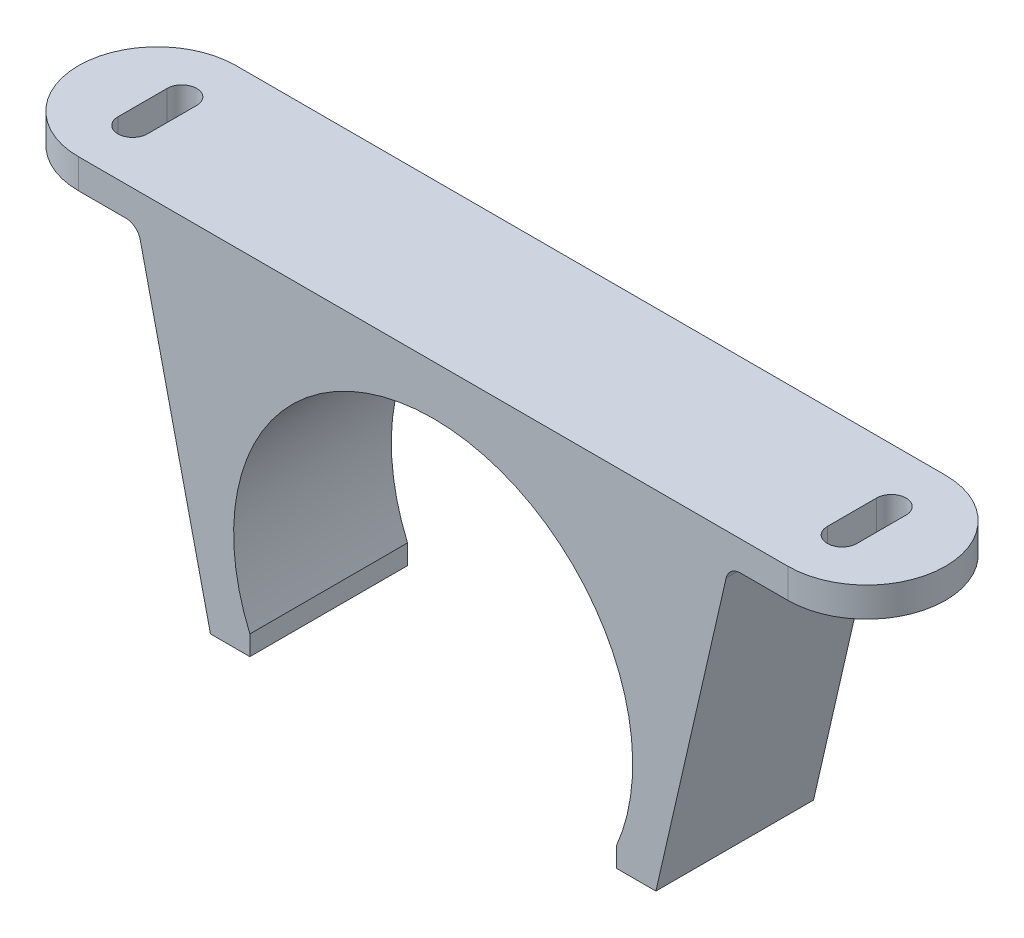
SolidWorks part; units mm, degrees
material "acero"
ref_plane "Alzado" through (0, 0, 0) normal (0, 0, 1) x (1, 0, 0)
ref_plane "Planta" through (0, 0, 0) normal (0, 1, 0) x (1, 0, 0)
ref_plane "Vista lateral" through (0, 0, 0) normal (1, 0, 0) x (0, 0, -1)
sketch "Croquis1" plane through (0, 0, 0) normal (0, 0, 1) x (1, 0, 0)
  line L0 (18.6028, -8) -> (18.6028, -10)
  line L1 (18.6028, -10) -> (22.6028, -10)
  line L2 (22.6028, -10) -> (30, 22.25)
  line L3 (30, 22.25) -> (-30, 22.25)
  line L4 (-30, 22.25) -> (-22.6028, -10)
  line L5 (-22.6028, -10) -> (-18.6028, -10)
  line L6 (-18.6028, -10) -> (-18.6028, -8)
  line L7 (0, 20.25) -> (0, 0) construction
  arc A0 (18.6028, -8) -> (-18.6028, -8) centre (0, 0) ccw
  point P1 (0, 22.25)
  point P8 (0, 20.25)
  point P13 (0, 0)
  dimension "D1" = 40.5
  dimension "D2" = 2
  dimension "D3" = 2
  dimension "D4" = 4
  dimension "D5" = 60
  dimension "D6" = 8
extrude "Saliente-Extruir1" add sketch "Croquis1" along normal blind 16
sketch "Croquis2" plane through (0, 22.25, 0) normal (0, 1, 0) x (1, 0, 0)
  line L0 (30, 0) -> (-30, 0) construction
  line L1 (30, -16) -> (-30, -16) construction
  line L2 (30, 0) -> (-30, 0)
  line L3 (30, -16) -> (-30, -16)
  line L4 (-30, 0) -> (-36, 0)
  line L5 (-30, -16) -> (-36, -16)
  line L6 (30, 0) -> (36, 0)
  line L7 (30, -16) -> (36, -16)
  line L8 (-36, -10.5) -> (-36, -5.5) construction
  line L9 (-37.5, -10.5) -> (-37.5, -5.5)
  line L10 (-34.5, -10.5) -> (-34.5, -5.5)
  line L11 (36, -10.5) -> (36, -5.5) construction
  line L12 (34.5, -10.5) -> (34.5, -5.5)
  line L13 (37.5, -10.5) -> (37.5, -5.5)
  arc A0 (-36, 0) -> (-36, -16) centre (-36, -8) ccw
  arc A1 (36, 0) -> (36, -16) centre (36, -8) cw
  arc A2 (-37.5, -10.5) -> (-34.5, -10.5) centre (-36, -10.5) ccw
  arc A3 (-34.5, -5.5) -> (-37.5, -5.5) centre (-36, -5.5) ccw
  arc A4 (34.5, -10.5) -> (37.5, -10.5) centre (36, -10.5) ccw
  arc A5 (37.5, -5.5) -> (34.5, -5.5) centre (36, -5.5) ccw
  point P13 (-36, -8)
  point P19 (36, -8)
  dimension "D3" = 1.5
  dimension "D1" = 6
  dimension "D2" = 5
extrude "Saliente-Extruir2" add sketch "Croquis2" along normal blind 3
fillet "Redondeo1" radius 1.5 2 edges
